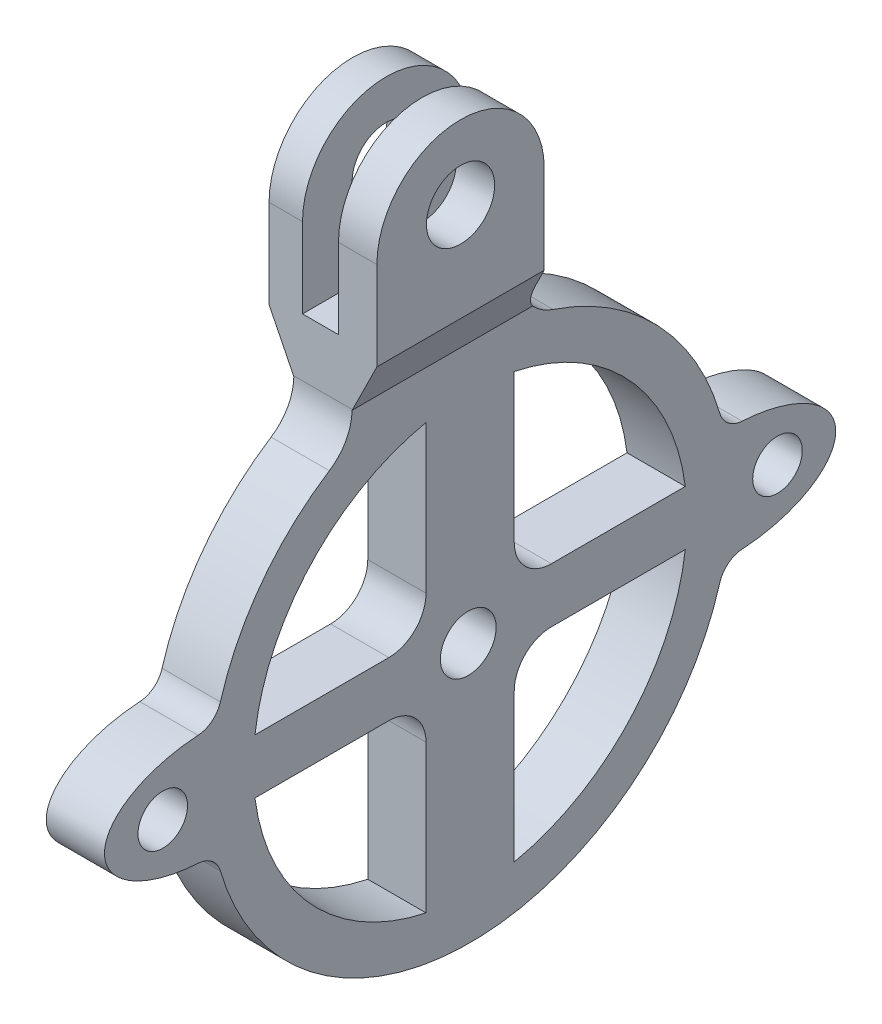
SolidWorks part; units mm, degrees
ref_plane "前视基准面" through (0, 0, 0) normal (0, 0, 1) x (1, 0, 0)
ref_plane "上视基准面" through (0, 0, 0) normal (0, 1, 0) x (1, 0, 0)
ref_plane "右视基准面" through (0, 0, 0) normal (1, 0, 0) x (0, 0, -1)
other "Configuration Table"
sketch "草图1" plane through (0, 0, 0) normal (1, 0, 0) x (0, 0, -1)
  line L0 (-3.5583, 17.1344) -> (-3.5583, 5.205)
  line L2 (3.5583, -17.1344) -> (3.5583, -5.205)
  line L4 (17.3605, 2.205) -> (6.5583, 2.205)
  line L6 (-17.3605, -2.205) -> (-6.5583, -2.205)
  line L8 (3.5583, 5.205) -> (3.5583, 17.1344)
  line L9 (-3.5583, -5.205) -> (-3.5583, -17.1344)
  line L10 (-6.5583, 2.205) -> (-17.3605, 2.205)
  line L11 (6.5583, -2.205) -> (17.3605, -2.205)
  line L14 (-9.5232, 32.1523) -> (-9.5232, 21.0267)
  line L16 (3.9768, 32.1523) -> (3.9768, 23.6933)
  arc A0 (-20.1525, -5.9057) -> (20.1525, -5.9057) centre (0, 0) ccw
  circle A1 centre (-24.8, 0) radius 2
  arc A3 (20.1525, 5.9057) -> (6.7005, 19.9023) centre (0, 0) ccw
  circle A4 centre (24.8, 0) radius 2
  arc A5 (3.5583, -17.1344) -> (17.3605, -2.205) centre (0, 0) ccw
  arc A6 (-3.5583, 17.1344) -> (-17.3605, 2.205) centre (0, 0) ccw
  arc A7 (-17.3605, -2.205) -> (-3.5583, -17.1344) centre (0, 0) ccw
  arc A8 (17.3605, 2.205) -> (3.5583, 17.1344) centre (0, 0) ccw
  arc A9 (-3.5583, -5.205) -> (-6.5583, -2.205) centre (-6.5583, -5.205) ccw
  arc A10 (3.5583, -5.205) -> (6.5583, -2.205) centre (6.5583, -5.205) cw
  arc A11 (3.5583, 5.205) -> (6.5583, 2.205) centre (6.5583, 5.205) ccw
  arc A12 (-3.5583, 5.205) -> (-6.5583, 2.205) centre (-6.5583, 5.205) cw
  arc A13 (-21.9526, 4.4717) -> (-20.1525, 5.9057) centre (-22.0718, 6.4681) ccw
  arc A14 (-21.9526, -4.4717) -> (-20.1525, -5.9057) centre (-22.0718, -6.4681) cw
  arc A15 (21.9526, -4.4717) -> (20.1525, -5.9057) centre (22.0718, -6.4681) ccw
  arc A16 (21.9526, 4.4717) -> (20.1525, 5.9057) centre (22.0718, 6.4681) cw
  arc A17 (-11.3595, 17.6625) -> (-20.1525, 5.9057) centre (0, 0) ccw
  arc A18 (3.9768, 32.1523) -> (-9.5232, 32.1523) centre (-2.7732, 32.1523) ccw
  arc A19 (-9.5232, 21.0267) -> (-11.3595, 17.6625) centre (-13.5232, 21.0267) cw
  arc A20 (6.7005, 19.9023) -> (3.9768, 23.6933) centre (7.9768, 23.6933) cw
  circle A21 centre (-2.7732, 32.9523) radius 2.75
  circle A22 centre (-0.15, 0) radius 2.25
  ellipse E0 centre (-21, 0) end of major axis (-29.5, 0) minor radius 4.5 (-21.9526, 4.4717) -> (-21.9526, -4.4717) ccw
  ellipse E1 centre (21, 0) end of major axis (12.5, 0) minor radius 4.5 (21.9526, 4.4717) -> (21.9526, -4.4717) cw
  point P36 (3.5583, -2.205)
  point P41 (-3.5583, 2.205)
  dimension "D1" = 42
  dimension "D2" = 4
  dimension "D3" = 35
  dimension "D4" = 22.8
  dimension "D5" = 3
  dimension "D8" = 3
  dimension "D9" = 3
  dimension "D10" = 3
  dimension "D11" = 2
  dimension "D12" = 2
  dimension "D13" = 2
  dimension "D14" = 2
  dimension "D18" = 4
  dimension "D17" = 4
  dimension "D20" = 19
  dimension "D21" = 5.5
  dimension "D23" = 8.5
  dimension "D24" = 22.8
  dimension "D25" = 22.65
  dimension "D26" = 4.5
  dimension "D6" = 9
  dimension "D7" = 8.5
  dimension "D15" = 7.1167
  dimension "D16" = 4.4101
  dimension "D19" = 13.5
  dimension "D22" = 0.8
extrude "凸台-拉伸2" add sketch "草图1" along normal blind 8.7
sketch "草图8" plane through (0, 0, 0) normal (0, 0, 1) x (1, 0, 0)
  line L0 (8.7, -21) -> (8.7, -5.9057) construction
  line L1 (0, -21) -> (2, -21)
  line L2 (0, -21) -> (0, 25)
  line L4 (2, -21) -> (2, 20.9689)
  line L5 (8.7, -21) -> (6.7, -21)
  line L6 (8.7, -21) -> (8.7, 25)
  line L8 (6.7, -21) -> (6.7, 20.9689)
  line L9 (8.7, 32.1523) -> (8.7, 21.0267) construction
  line L10 (2.7, 38.9023) -> (5.6, 38.9023)
  line L11 (2.7, 38.9023) -> (2.7, 25.7023)
  line L12 (2.7, 25.7023) -> (5.6, 25.7023)
  line L13 (5.6, 38.9023) -> (5.6, 25.7023)
  line L14 (0, 25) -> (2, 20.9689)
  line L16 (8.7, 25) -> (6.7, 20.9689)
  dimension "D1" = 4.5
  dimension "D2" = 4.5
  dimension "D3" = 2
  dimension "D4" = 2
  dimension "D5" = 13.2
  dimension "D6" = 2.9
  dimension "D7" = 3.1
  dimension "D8" = 41.9689
  dimension "4" = 46
  dimension "D9" = 46
  dimension "D10" = 41.9689
extrude "切除-拉伸11" cut sketch "草图8" against normal mid plane 60
